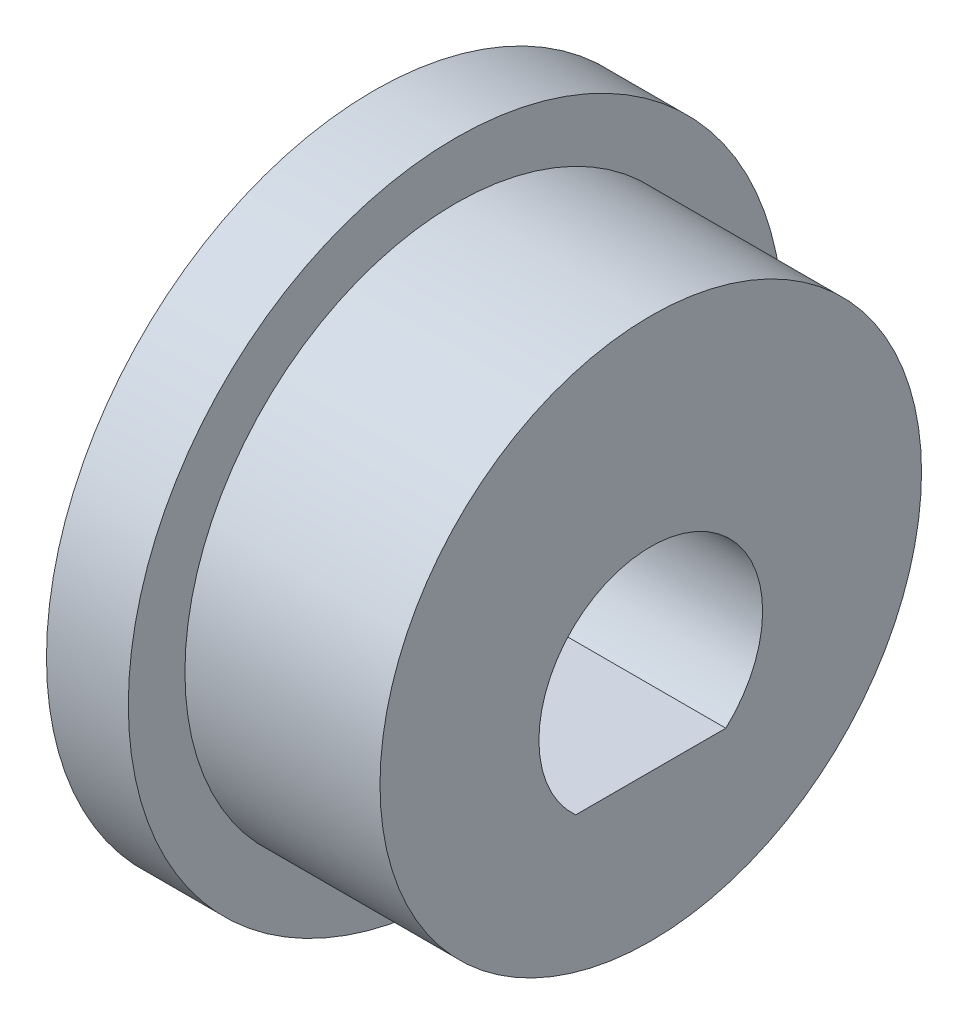
SolidWorks part; units mm, degrees
ref_plane "Ebene vorne" through (0, 0, 0) normal (0, 0, 1) x (1, 0, 0)
ref_plane "Ebene oben" through (0, 0, 0) normal (0, 1, 0) x (1, 0, 0)
ref_plane "Ebene rechts" through (0, 0, 0) normal (1, 0, 0) x (0, 0, -1)
sketch "Skizze1" plane through (0, 0, 0) normal (1, 0, 0) x (0, 0, -1)
  circle A0 centre (0, 1.5) radius 9.925
  dimension "D1" = 19.85
  dimension "D2" = 1.5
extrude "Aufsatz-Linear austragen1" add sketch "Skizze1" along normal blind 7.15
sketch "Skizze2" plane through (0, 0, 0) normal (-1, 0, 0) x (0, 0, 1)
  circle A0 centre (0, 1.5) radius 12
  dimension "D1" = 24
extrude "Aufsatz-Linear austragen2" add sketch "Skizze2" along normal blind 3
sketch "Skizze3" plane through (7.15, 0, 0) normal (1, 0, 0) x (0, 0, -1)
  line L0 (2.75, -3.041) -> (-2.75, -3.041)
  arc A0 (2.75, -3.041) -> (-2.75, -3.041) centre (0, 0) ccw
  dimension "D1" = 4.1
  dimension "D2" = 5.5
extrude "Schnitt-Linear austragen1" cut sketch "Skizze3" against normal through all and the other way through all
